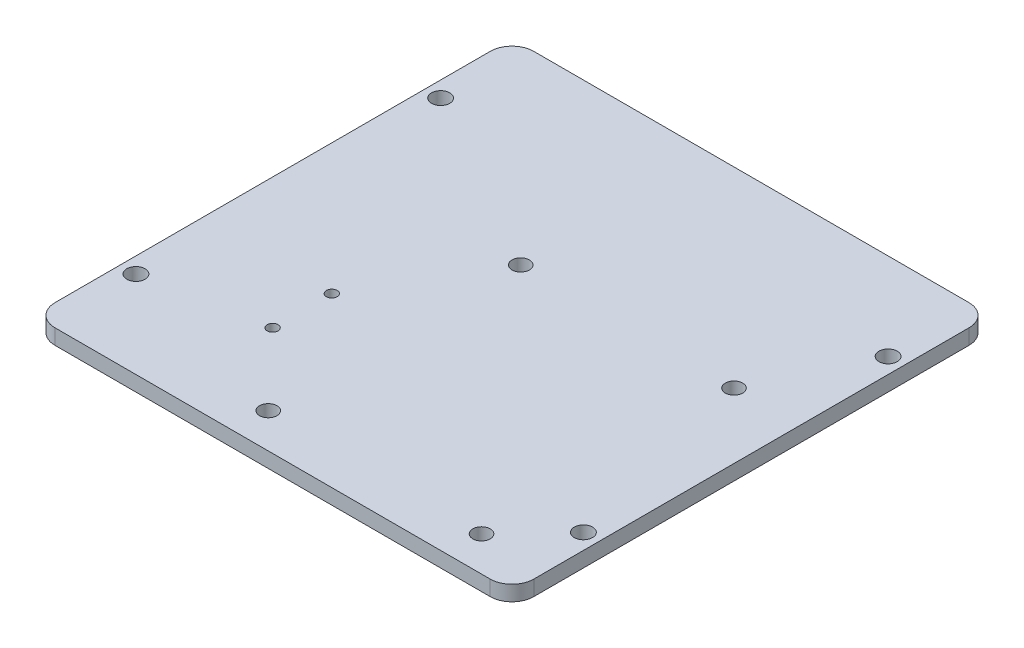
SolidWorks part; units mm, degrees
ref_plane "Plan de face" through (0, 0, 0) normal (0, 0, 1) x (1, 0, 0)
ref_plane "Plan de dessus" through (0, 0, 0) normal (0, 1, 0) x (1, 0, 0)
ref_plane "Plan de droite" through (0, 0, 0) normal (1, 0, 0) x (0, 0, -1)
sketch "Esquisse1" plane through (0, 0, 0) normal (0, 1, 0) x (1, 0, 0)
  line L0 (0, -55) -> (0, 55) construction
  line L1 (-55, -55) -> (55, -55)
  line L2 (-55, -55) -> (-55, 55)
  line L3 (-55, 55) -> (55, 55)
  line L4 (55, -55) -> (55, 55)
  line L5 (-55, -55) -> (55, 55) construction
  line L6 (-55, 55) -> (55, -55) construction
  line L7 (-55, 0) -> (55, 0) construction
  line L8 (-55, 38.6) -> (-51.4, 38.6)
  line L9 (-51.4, 31.4) -> (-55, 31.4)
  line L10 (-55, 31.4) -> (-55, 38.6)
  circle A0 centre (-51.4, 35) radius 2.1
  circle A1 centre (51.4, 35) radius 2.1
  circle A2 centre (51.4, -35) radius 2.1
  circle A3 centre (-51.4, -35) radius 2.1
  arc A4 (-51.4, 38.6) -> (-51.4, 31.4) centre (-51.4, 35) cw
  point P0 (0, 0)
  point P22 (-47.8, 35)
  dimension "D4" = 4.2
  dimension "D5" = 7.2
  dimension "D1" = 110
  dimension "D2" = 20
  dimension "D3" = 7.2
extrude "Boss.-Extru.1" add sketch "Esquisse1" along normal blind 3.5 contours L8 A4 L9 L2 L1 L4 L3 A3 A2 A1 | A4 L8 L2 L9 A0
fillet "Congé1" radius 5 4 edges at (-55, 1.75, -55) (-55, 1.75, 55) (55, 1.75, 55) (55, 1.75, -55)
sketch "Esquisse2" [suppressed] plane through (0, 3.5, 0) normal (0, 1, 0) x (1, 0, 0)
  line L0 (-38.7, 55) -> (-31.3, 55)
  line L2 (-31.3, 55) -> (-31.3, 51.3)
  line L3 (-38.7, 51.3) -> (-38.7, 55)
  line L4 (-55, -50) -> (-55, 50) construction
  line L5 (-55, 0) -> (55, 0) construction
  line L6 (-31.3, -55) -> (-31.3, -51.3)
  line L7 (-38.7, -55) -> (-31.3, -55)
  line L8 (-38.7, -51.3) -> (-38.7, -55)
  line L9 (0, -55) -> (0, 55) construction
  line L10 (31.3, -55) -> (31.3, -51.3)
  line L11 (38.7, -55) -> (31.3, -55)
  line L12 (38.7, -51.3) -> (38.7, -55)
  line L13 (31.3, 55) -> (31.3, 51.3)
  line L14 (38.7, 55) -> (31.3, 55)
  line L15 (38.7, 51.3) -> (38.7, 55)
  line L17 (-50, 55) -> (50, 55) construction
  arc A0 (-31.3, 51.3) -> (-38.7, 51.3) centre (-35, 51.3) cw
  arc A1 (-31.3, -51.3) -> (-38.7, -51.3) centre (-35, -51.3) ccw
  arc A2 (31.3, -51.3) -> (38.7, -51.3) centre (35, -51.3) cw
  arc A3 (31.3, 51.3) -> (38.7, 51.3) centre (35, 51.3) ccw
  point P28 (-35, 47.6)
  dimension "D1" = 7.4
  dimension "D2" = 7.4
  dimension "D3" = 20
extrude "Enlèv. mat.-Extru.1" [suppressed] cut sketch "Esquisse2" against normal through all
sketch "Esquisse3" plane through (0, 3.5, 0) normal (0, 1, 0) x (1, 0, 0)
  line L0 (55, -50) -> (55, 50) construction
  line L3 (40, 11) -> (40, -47) construction
  line L4 (-50, -55) -> (50, -55) construction
  circle A0 centre (40, 11) radius 2
  circle A1 centre (40, -47) radius 2
  circle A2 centre (-9, -47) radius 2
  circle A3 centre (-9, 11) radius 2
  dimension "D2" = 4
  dimension "D1" = 58
  dimension "D3" = 49
  dimension "D4" = 15
  dimension "D5" = 8
extrude "Trous RPI" cut sketch "Esquisse3" against normal through all
sketch "Esquisse4" [suppressed] plane through (0, 0, 0) normal (0, -1, 0) x (1, 0, 0)
  line L0 (-7.5, -1.5) -> (-7.5, 9.5)
  line L1 (-7.5, 9.5) -> (-15.5, 9.5)
  line L2 (-15.5, 9.5) -> (-15.5, 27.5)
  line L3 (-15.5, 27.5) -> (-20.5, 27.5)
  line L20 (-20.5, 27.5) -> (-20.5, -22.5)
  line L21 (-20.5, -22.5) -> (-15.5, -22.5)
  line L22 (-15.5, -22.5) -> (-15.5, -8.5)
  line L23 (-15.5, -8.5) -> (-7.5, -8.5)
  line L24 (-7.5, -8.5) -> (-7.5, -2.5)
  line L29 (-9, 28) -> (-9, -28) construction
  line L76 (-40.5, -22.5) -> (-40.5, 27.5)
  line L77 (-40.5, 27.5) -> (-45.5, 27.5)
  line L78 (-45.5, 27.5) -> (-45.5, -22.5)
  line L79 (-45.5, -22.5) -> (-40.5, -22.5)
  line L81 (-7.5, -1.5) -> (-7.5, -2.5)
  line L82 (-15.5, -1.5) -> (-7.5, -1.5) construction
  line L83 (-7.5, -2.5) -> (-15.5, -2.5) construction
  line L84 (55, 50) -> (55, -50) construction
  line L85 (38.7, 55) -> (50, 55) construction
  line L86 (-55, 50) -> (-55, -50) construction
  line L112 (8, 12) -> (47, 12) construction
  line L113 (27.5, 12) -> (27.5, 42.6) construction
  line L129 (5, 15) -> (8, 15)
  line L130 (5, 15) -> (5, 9)
  line L131 (5, 9) -> (8, 9)
  line L132 (8, 15) -> (8, 9)
  line L133 (47, 15) -> (50, 15)
  line L134 (47, 15) -> (47, 9)
  line L135 (47, 9) -> (50, 9)
  line L136 (50, 15) -> (50, 9)
  line L137 (5, -15) -> (8, -15)
  line L138 (5, -15) -> (5, -9)
  line L139 (5, -9) -> (8, -9)
  line L140 (8, -15) -> (8, -9)
  line L141 (50, -15) -> (47, -15)
  line L142 (50, -15) -> (50, -9)
  line L143 (50, -9) -> (47, -9)
  line L144 (47, -15) -> (47, -9)
  line L227 (22.5, 42.6) -> (32.5, 42.6) construction
  line L228 (22.5, 45.1) -> (32.5, 45.1)
  line L229 (22.5, 40.1) -> (32.5, 40.1)
  line L383 (-9, 0) -> (-9, 8) construction
  line L384 (-9, 8) -> (-17, 8) construction
  line L385 (-17, 8) -> (-17, 26) construction
  line L386 (-17, 26) -> (-19, 26) construction
  line L387 (-19, 26) -> (-19, -21) construction
  line L388 (-19, -21) -> (-17, -21) construction
  line L389 (-17, -21) -> (-17, -7) construction
  line L390 (-17, -7) -> (-9, -7) construction
  line L391 (-9, -7) -> (-9, -4) construction
  line L392 (-9, -4) -> (-17, -4) construction
  line L393 (-17, -4) -> (-17, 0) construction
  line L394 (-17, 0) -> (-9, 0) construction
  line L395 (-42, -21) -> (-42, 26) construction
  line L396 (-42, 26) -> (-44, 26) construction
  line L397 (-44, 26) -> (-44, -21) construction
  line L398 (-44, -21) -> (-42, -21) construction
  line L399 (-9, 0) -> (-9, 8)
  line L400 (-9, 8) -> (-17, 8)
  line L401 (-17, 8) -> (-17, 26)
  line L402 (-17, 26) -> (-19, 26)
  line L403 (-19, 26) -> (-19, -21)
  line L404 (-19, -21) -> (-17, -21)
  line L405 (-17, -21) -> (-17, -7)
  line L406 (-17, -7) -> (-9, -7)
  line L407 (-9, -7) -> (-9, -4)
  line L408 (-9, -4) -> (-17, -4)
  line L409 (-17, -4) -> (-17, 0)
  line L410 (-17, 0) -> (-9, 0)
  line L411 (-42, -21) -> (-42, 26)
  line L412 (-42, 26) -> (-44, 26)
  line L413 (-44, 26) -> (-44, -21)
  line L414 (-44, -21) -> (-42, -21)
  line L415 (-15.5, -2.5) -> (-15.5, -1.5) construction
  circle A3 centre (-45, -28) radius 1.25
  circle A5 centre (-9, 28) radius 1.25
  circle A7 centre (-9, -28) radius 1.25
  arc A9 (31.3, 51.3) -> (38.7, 51.3) centre (35, 51.3) ccw construction
  arc A24 (22.5, 45.1) -> (22.5, 40.1) centre (22.5, 42.6) ccw
  arc A25 (32.5, 40.1) -> (32.5, 45.1) centre (32.5, 42.6) ccw
  point P1 (-9, 0)
  point P13 (35, 47.6)
  point P50 (27.5, 42.6)
  point P57 (48.5, 9)
  dimension "D12" = 2.5
  dimension "D5" = 3
  dimension "D6" = 45
  dimension "D7" = 30
  dimension "D8" = 5
  dimension "D9" = 40
  dimension "D10" = 6
  dimension "D11" = 5
  dimension "D13" = 5
  dimension "D14" = 10
  dimension "D2" = 56
  dimension "D3" = 36
  dimension "D4" = 10
  dimension "D15" = 1.5
extrude "Enlèv. mat.-Extru.2" [suppressed] cut sketch "Esquisse4" against normal through all
sketch "Esquisse5" plane through (0, 0, 0) normal (0, -1, 0) x (-1, 0, 0)
  line L0 (55, -50) -> (55, 50) construction
  line L3 (50, -55) -> (-50, -55) construction
  circle A0 centre (25, -30) radius 1.25
  circle A1 centre (25, -16.4) radius 1.25
  dimension "D2" = 2.5
  dimension "D1" = 13.6
  dimension "D3" = 25
  dimension "D4" = 30
extrude "Trous ICM" cut sketch "Esquisse5" against normal through all
